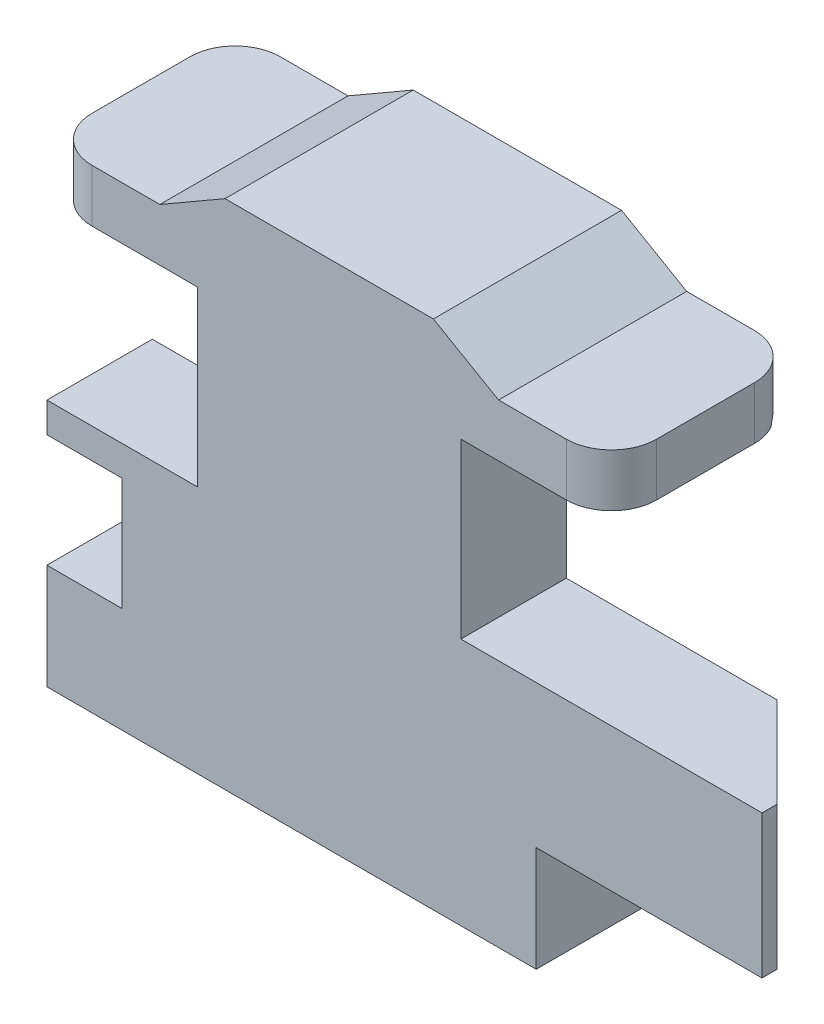
SolidWorks part; units mm, degrees
ref_plane "Front Plane" through (0, 0, 0) normal (0, 0, 1) x (1, 0, 0)
ref_plane "Top Plane" through (0, 0, 0) normal (0, 1, 0) x (1, 0, 0)
ref_plane "Right Plane" through (0, 0, 0) normal (1, 0, 0) x (0, 0, -1)
ref_plane "Plane1" through (0, 6.6, 0) normal (0, 1, 0) x (1, 0, 0)
sketch "Sketch1" plane through (0, 6.6, 0) normal (0, 1, 0) x (1, 0, 0)
  line L0 (-21.6252, 0.4) -> (-24.0252, 2.8)
  line L1 (-24.0252, 2.8) -> (-40.6252, 2.8)
  line L2 (-40.6252, 2.8) -> (-40.6252, 0)
  line L3 (-40.6252, 0) -> (-21.6252, 0)
  line L4 (-21.6252, 0) -> (-21.6252, 0.4)
extrude "Boss-Extrude1" add sketch "Sketch1" against normal blind 3.8
sketch "Sketch2" plane through (0, 6.6, 0) normal (0, 1, 0) x (-1, 0, 0)
  line L0 (29.6252, -2.8) -> (29.6252, 0)
  line L1 (29.6252, 0) -> (40.6252, 0)
  line L2 (40.6252, 0) -> (40.6252, -2.8)
  line L3 (40.6252, -2.8) -> (29.6252, -2.8)
extrude "Boss-Extrude2" add sketch "Sketch2" along normal blind 7
sketch "Sketch3" plane through (0, 0, 0) normal (0, 0, 1) x (1, 0, 0)
  line L0 (-36.6252, 11.2) -> (-40.6252, 11.2)
  line L1 (-40.6252, 11.2) -> (-40.6252, 2.8)
  line L2 (-40.6252, 2.8) -> (-36.6252, 2.8)
  line L3 (-36.6252, 2.8) -> (-36.6252, 11.2)
extrude "Cut-Extrude1" cut sketch "Sketch3" against normal through all
sketch "Sketch4" plane through (0, 0, -2.8) normal (0, 0, -1) x (-1, 0, 0)
  line L0 (29.6252, 13.6) -> (40.6252, 13.6)
  line L1 (40.6252, 13.6) -> (40.6252, 11.2)
  line L2 (40.6252, 11.2) -> (29.6252, 11.2)
  line L3 (29.6252, 11.2) -> (29.6252, 13.6)
extrude "Boss-Extrude3" add sketch "Sketch4" along normal blind 2.2
sketch "Sketch5" plane through (-29.6252, 0, 0) normal (1, 0, 0) x (0, 0, -1)
  line L0 (5, 11.2) -> (0, 11.2)
  line L1 (0, 11.2) -> (0, 13.6)
  line L2 (0, 13.6) -> (5, 13.6)
  line L3 (5, 13.6) -> (5, 11.2)
extrude "Boss-Extrude4" add sketch "Sketch5" along normal blind 4
sketch "Sketch6" plane through (0, 2.8, 0) normal (0, -1, 0) x (1, 0, 0)
  line L0 (-36.6252, 0) -> (-27.6252, 0)
  line L1 (-27.6252, 0) -> (-27.6252, -2.8)
  line L2 (-27.6252, -2.8) -> (-36.6252, -2.8)
  line L3 (-36.6252, -2.8) -> (-36.6252, 0)
extrude "Boss-Extrude5" add sketch "Sketch6" along normal blind 2.8
sketch "Sketch7" plane through (-36.6252, 0, 0) normal (-1, 0, 0) x (0, 0, 1)
  line L0 (-2.8, 0) -> (-2.8, 6.6)
  line L1 (-2.8, 6.6) -> (0, 6.6)
  line L2 (0, 6.6) -> (0, 0)
  line L3 (0, 0) -> (-2.8, 0)
extrude "Boss-Extrude6" add sketch "Sketch7" along normal blind 4
sketch "Sketch8" plane through (0, 0, -5) normal (0, 0, -1) x (-1, 0, 0)
  line L0 (35.8932, 13.6) -> (35.8932, 12.6)
  line L1 (35.8932, 12.6) -> (40.6252, 12.6)
  line L2 (40.6252, 12.6) -> (40.6252, 13.6)
  line L3 (40.6252, 13.6) -> (35.8932, 13.6)
extrude "Cut-Extrude2" cut sketch "Sketch8" against normal through all
sketch "Sketch9" plane through (0, 0, 0) normal (0, 0, 1) x (1, 0, 0)
  line L0 (-30.3573, 13.6) -> (-30.3573, 12.6)
  line L1 (-30.3573, 12.6) -> (-25.6252, 12.6)
  line L2 (-25.6252, 12.6) -> (-25.6252, 13.6)
  line L3 (-25.6252, 13.6) -> (-30.3573, 13.6)
extrude "Cut-Extrude3" cut sketch "Sketch9" against normal through all
sketch "Sketch10" plane through (0, 0, -2.8) normal (0, 0, -1) x (-1, 0, 0)
  line L0 (40.6252, 2.8) -> (40.6252, 5.8)
  line L1 (40.6252, 5.8) -> (38.6252, 5.8)
  line L2 (38.6252, 5.8) -> (38.6252, 2.8)
  line L3 (38.6252, 2.8) -> (40.6252, 2.8)
extrude "Cut-Extrude4" cut sketch "Sketch10" against normal through all
draft "Draft1" type of draft neutral plane draft angle 60 faces to draft 2 face at (-30.3573, 13.1, -2.5) face at (-35.8932, 13.1, -2.5) neutral plane through (0, 13.6, 0) neutral plane normal (0, 1, 0) parameters "D1"=60
chamfer "Chamfer1" distance 0.6 angle 45 1 edges at (-33.1252, 11.2, -5)
fillet "Fillet1" radius 1.2 4 edges at (-25.6252, 12.2, -5) (-25.6252, 11.9, 0) (-40.6252, 12.2, -5) (-40.6252, 11.9, 0)
